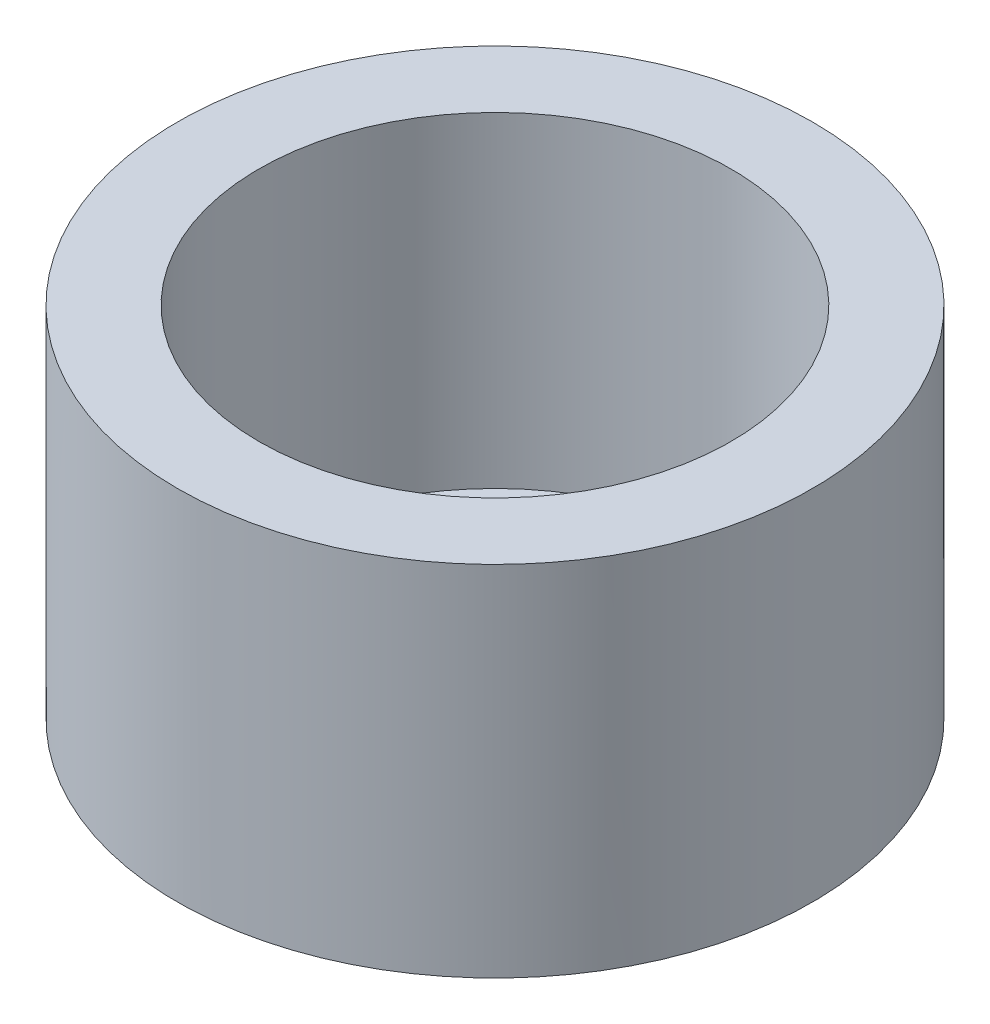
SolidWorks part; units mm, degrees
ref_plane "Front Plane" through (0, 0, 0) normal (0, 0, 1) x (1, 0, 0)
ref_plane "Top Plane" through (0, 0, 0) normal (0, 1, 0) x (1, 0, 0)
ref_plane "Right Plane" through (0, 0, 0) normal (1, 0, 0) x (0, 0, -1)
sketch "Sketch2" plane through (0, 0, 0) normal (0, 1, 0) x (1, 0, 0)
  circle A0 centre (0, 0) radius 14.5
  circle A1 centre (0, 0) radius 19.5
  dimension "D1" = 29
  dimension "D2" = 5
extrude "Boss-Extrude1" add sketch "Sketch2" along normal blind 20
sketch "Sketch3" plane through (0, 0, 0) normal (0, -1, 0) x (1, 0, 0)
  circle A0 centre (0, 0) radius 19.5
extrude "Boss-Extrude2" add sketch "Sketch3" along normal blind 2
sketch "Sketch4" plane through (0, -2, 0) normal (0, -1, 0) x (1, 0, 0)
  circle A0 centre (0, 0) radius 2.85
  dimension "D1" = 5.7
extrude "Boss-Extrude3" add sketch "Sketch4" along normal blind 6
